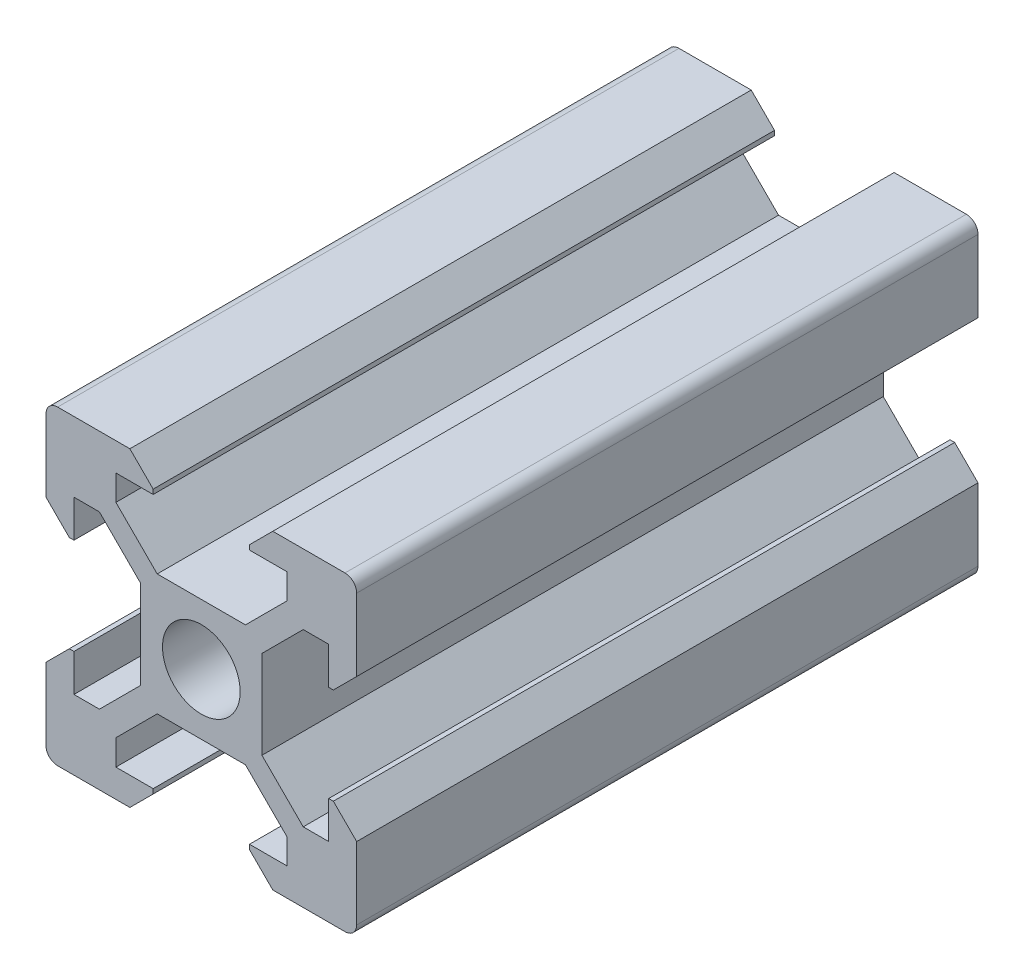
SolidWorks part; units mm, degrees
other "Markup1"
sketch "Sketch1" plane through (10, 10, 480) normal (0.5774, 0.5773, 0.5774) x (0.7071, 0, -0.7071)
ref_plane "Alzado" through (0, 0, 0) normal (0, 0, 1) x (1, 0, 0)
ref_plane "Planta" through (0, 0, 0) normal (0, 1, 0) x (1, 0, 0)
ref_plane "Vista lateral" through (0, 0, 0) normal (1, 0, 0) x (0, 0, -1)
sketch "Croquis1" plane through (0, 0, 0) normal (0, 0, 1) x (1, 0, 0)
  line L0 (-4.6, 10) -> (-3.1, 8.5)
  line L3 (-4.6, 10) -> (-9.25, 10)
  line L5 (-3.1, 8.5) -> (-3.1, 8.2)
  line L6 (-3.1, 8.2) -> (-5.5, 8.2)
  line L7 (-5.5, 8.2) -> (-5.5, 6.5607)
  line L8 (-5.5, 6.5607) -> (-2.84, 3.9007)
  line L9 (-2.84, 3.9007) -> (0, 3.9007)
  line L10 (0, 0) -> (-15.3499, 15.3499) construction
  line L11 (-3.9007, 2.84) -> (-3.9007, 0)
  line L12 (-6.5607, 5.5) -> (-3.9007, 2.84)
  line L13 (-8.2, 5.5) -> (-6.5607, 5.5)
  line L14 (-8.2, 3.1) -> (-8.2, 5.5)
  line L15 (-8.5, 3.1) -> (-8.2, 3.1)
  line L16 (-10, 4.6) -> (-10, 9.25)
  line L17 (-10, 4.6) -> (-8.5, 3.1)
  line L18 (10, 4.6) -> (8.5, 3.1)
  line L19 (10, 4.6) -> (10, 9.25)
  line L20 (8.5, 3.1) -> (8.2, 3.1)
  line L21 (8.2, 3.1) -> (8.2, 5.5)
  line L22 (8.2, 5.5) -> (6.5607, 5.5)
  line L23 (6.5607, 5.5) -> (3.9007, 2.84)
  line L24 (3.9007, 2.84) -> (3.9007, 0)
  line L25 (5.5, 6.5607) -> (2.84, 3.9007)
  line L26 (5.5, 8.2) -> (5.5, 6.5607)
  line L27 (3.1, 8.2) -> (5.5, 8.2)
  line L28 (3.1, 8.5) -> (3.1, 8.2)
  line L29 (4.6, 10) -> (9.25, 10)
  line L30 (4.6, 10) -> (3.1, 8.5)
  line L31 (2.84, 3.9007) -> (0, 3.9007)
  line L32 (4.6, -10) -> (3.1, -8.5)
  line L33 (4.6, -10) -> (9.25, -10)
  line L34 (3.1, -8.5) -> (3.1, -8.2)
  line L35 (3.1, -8.2) -> (5.5, -8.2)
  line L36 (5.5, -8.2) -> (5.5, -6.5607)
  line L37 (5.5, -6.5607) -> (2.84, -3.9007)
  line L38 (2.84, -3.9007) -> (0, -3.9007)
  line L39 (6.5607, -5.5) -> (3.9007, -2.84)
  line L40 (8.2, -5.5) -> (6.5607, -5.5)
  line L41 (8.2, -3.1) -> (8.2, -5.5)
  line L42 (8.5, -3.1) -> (8.2, -3.1)
  line L43 (10, -4.6) -> (10, -9.25)
  line L44 (10, -4.6) -> (8.5, -3.1)
  line L45 (3.9007, -2.84) -> (3.9007, 0)
  line L46 (-10, -4.6) -> (-8.5, -3.1)
  line L47 (-10, -4.6) -> (-10, -9.25)
  line L48 (-8.5, -3.1) -> (-8.2, -3.1)
  line L49 (-8.2, -3.1) -> (-8.2, -5.5)
  line L50 (-8.2, -5.5) -> (-6.5607, -5.5)
  line L51 (-6.5607, -5.5) -> (-3.9007, -2.84)
  line L52 (-3.9007, -2.84) -> (-3.9007, 0)
  line L53 (-5.5, -6.5607) -> (-2.84, -3.9007)
  line L54 (-5.5, -8.2) -> (-5.5, -6.5607)
  line L55 (-3.1, -8.2) -> (-5.5, -8.2)
  line L56 (-3.1, -8.5) -> (-3.1, -8.2)
  line L57 (-4.6, -10) -> (-9.25, -10)
  line L58 (-4.6, -10) -> (-3.1, -8.5)
  line L59 (-2.84, -3.9007) -> (0, -3.9007)
  circle A0 centre (0, 0) radius 2.5
  arc A1 (-9.25, 10) -> (-10, 9.25) centre (-9.25, 9.25) ccw
  arc A2 (10, 9.25) -> (9.25, 10) centre (9.25, 9.25) ccw
  arc A3 (9.25, -10) -> (10, -9.25) centre (9.25, -9.25) ccw
  arc A4 (-10, -9.25) -> (-9.25, -10) centre (-9.25, -9.25) ccw
  point P18 (-10, 10)
  point P37 (10, 10)
  point P55 (10, -10)
  point P73 (-10, -10)
  point P79 (0, 0)
  dimension "D1" = 5
  dimension "D5" = 0.75
  dimension "D2" = 10
  dimension "D3" = 10
  dimension "D4" = 4.6
  dimension "D6" = 5.5
  dimension "D7" = 135
  dimension "D8" = 0.75
  dimension "D9" = 225
  dimension "D10" = 2.84
  dimension "D11" = 1.8
  dimension "D12" = 3.1
  dimension "D13" = 4
extrude "Saliente-Extruir1" add sketch "Croquis1" along normal blind 480
sketch "Sketch2" plane through (0, 0, 0) normal (1, 0, 0) x (0, 0, -1)
  line L0 (-440, 49.0269) -> (-440, -60.8966) construction
  line L1 (-440, -18.7044) -> (440, -18.7044)
  line L2 (-440, -18.7044) -> (-440, 18.7044)
  line L3 (-440, 18.7044) -> (440, 18.7044)
  line L4 (440, -18.7044) -> (440, 18.7044)
  line L5 (-440, -18.7044) -> (440, 18.7044) construction
  line L6 (-440, 18.7044) -> (440, -18.7044) construction
  line L7 (-480, -2.84) -> (-480, 2.84) construction
  point P0 (0, 0)
  dimension "D1" = 40
extrude "Cut-Extrude1" cut sketch "Sketch2" against normal blind 46 and the other way blind 47 contours L2 L1 L4 L3
